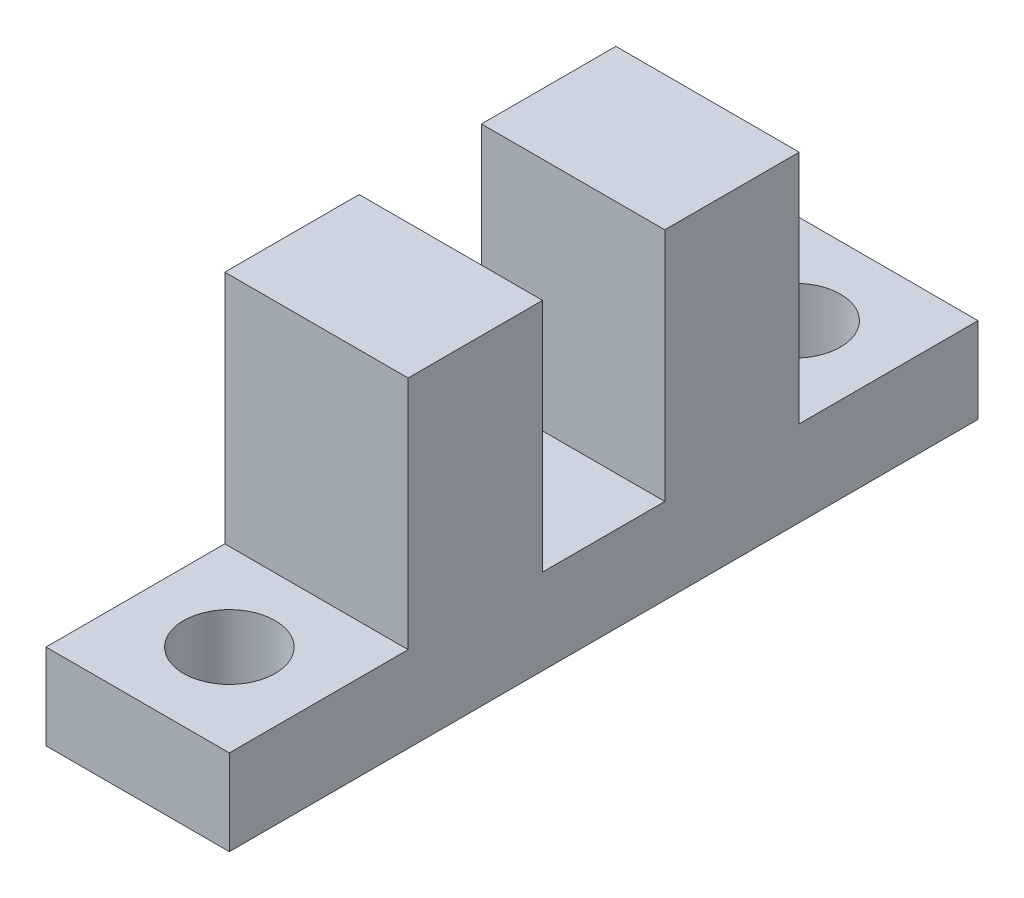
SolidWorks part; units mm, degrees
ref_plane "前基準面" through (0, 0, 0) normal (0, 0, 1) x (1, 0, 0)
ref_plane "上基準面" through (0, 0, 0) normal (0, 1, 0) x (1, 0, 0)
ref_plane "右基準面" through (0, 0, 0) normal (1, 0, 0) x (0, 0, -1)
sketch "草圖1" plane through (0, 0, 0) normal (1, 0, 0) x (0, 0, -1)
  line L0 (-2, 10.5) -> (2, 10.5) construction
  line L1 (-12.25, 0) -> (12.25, 0)
  line L2 (-12.25, 0) -> (-12.25, 2.8)
  line L3 (-12.25, 2.8) -> (-6.4, 2.8)
  line L4 (12.25, 0) -> (12.25, 2.8)
  line L5 (-12.25, 0) -> (12.25, 2.8) construction
  line L6 (-12.25, 2.8) -> (12.25, 0) construction
  line L8 (2, 2.8) -> (2, 10.5)
  line L9 (2, 10.5) -> (6.4, 10.5)
  line L10 (6.4, 2.8) -> (6.4, 10.5)
  line L11 (6.4, 2.8) -> (12.25, 2.8)
  line L12 (-2, 2.8) -> (-2, 10.5)
  line L13 (-2, 10.5) -> (-6.4, 10.5)
  line L14 (-6.4, 2.8) -> (-6.4, 10.5)
  line L15 (0, 10.5) -> (0, 1.4) construction
  line L16 (-2, 2.8) -> (2, 2.8)
  point P0 (0, 1.4)
  dimension "D1" = 24.5
  dimension "D2" = 4
  dimension "D3" = 4.4
  dimension "D4" = 4.4
  dimension "D5" = 2.8
  dimension "D6" = 10.5
extrude "填料-伸長1" add sketch "草圖1" along normal blind 6
sketch "草圖2" plane through (0, 2.8, 0) normal (0, 1, 0) x (1, 0, 0)
  line L0 (3, 9.25) -> (3, 12.25) construction
  line L1 (6, 12.25) -> (0, 12.25) construction
  circle A0 centre (3, 9.25) radius 1.5
  dimension "D1" = 3
  dimension "D2" = 9.25
extrude "除料-伸長1" cut sketch "草圖2" against normal through all
mirror "鏡射1" about plane through (0, 0, 0) normal (0, 0, 1) of "除料-伸長1"
